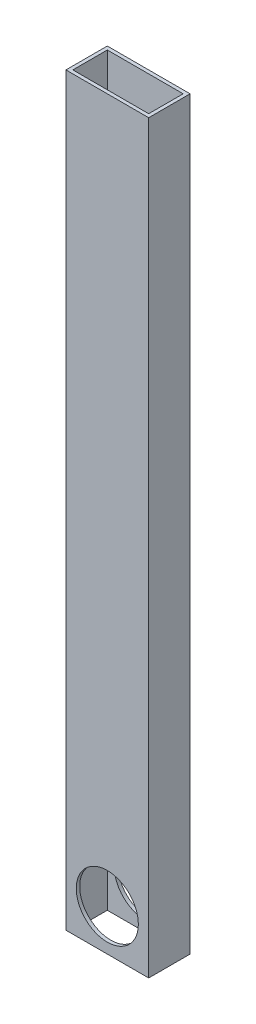
SolidWorks part; units mm, degrees
ref_plane "Front Plane" through (0, 0, 0) normal (0, 0, 1) x (1, 0, 0)
ref_plane "Top Plane" through (0, 0, 0) normal (0, 1, 0) x (1, 0, 0)
ref_plane "Right Plane" through (0, 0, 0) normal (1, 0, 0) x (0, 0, -1)
sketch "Sketch1" plane through (0, 0, 0) normal (0, 1, 0) x (1, 0, 0)
  line L1 (0, 0) -> (38.1, 0)
  line L2 (0, 0) -> (0, 19.05)
  line L3 (0, 19.05) -> (38.1, 19.05)
  line L4 (38.1, 0) -> (38.1, 19.05)
  dimension "D1" = 19.05
  dimension "D2" = 38.1
extrude "Extrude-Thin1" add sketch "Sketch1" along normal blind 342.9 thin thin type one direction reverse wall 1.5875
sketch "Sketch3" plane through (0, 0, 0) normal (0, 0, 1) x (1, 0, 0)
  line L0 (0, 342.9) -> (0, 0) construction
  line L1 (0, 0) -> (38.1, 0) construction
  circle A0 centre (19.05, 19.05) radius 14.2875
  dimension "D1" = 28.575
  dimension "D3" = 19.05
  dimension "D2" = 19.05
extrude "Cut-Extrude2" cut sketch "Sketch3" against normal through all
